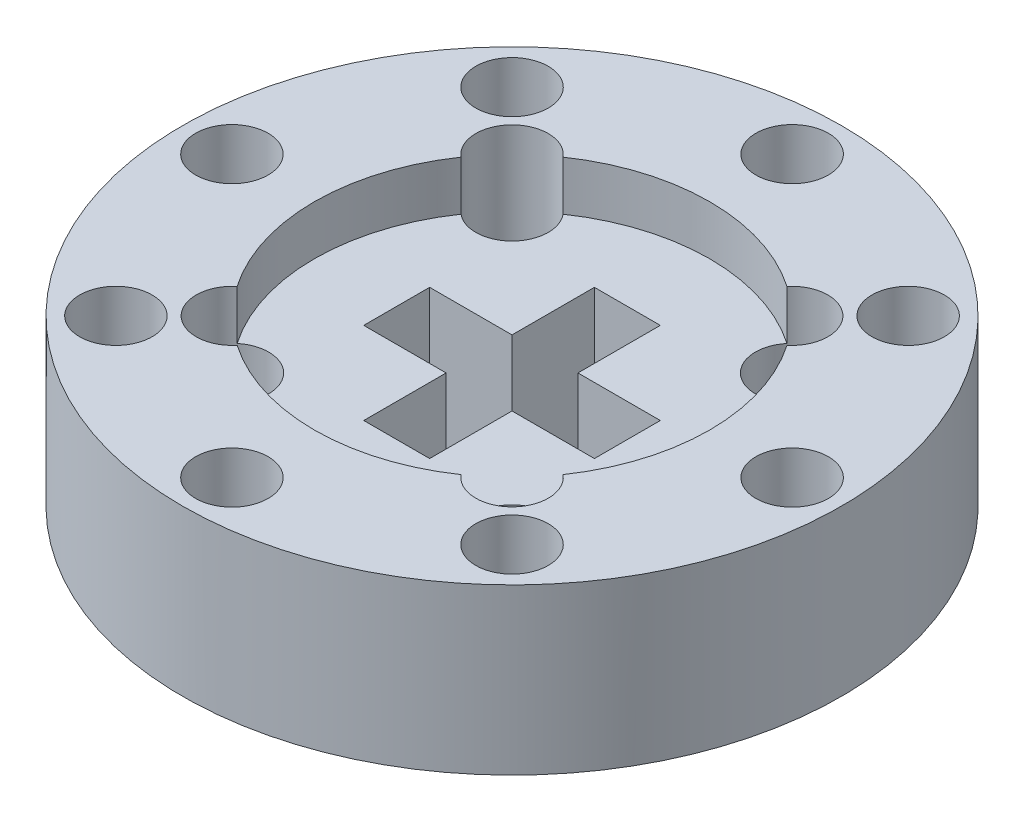
SolidWorks part; units mm, degrees
ref_plane "前视基准面" through (0, 0, 0) normal (0, 0, 1) x (1, 0, 0)
ref_plane "上视基准面" through (0, 0, 0) normal (0, 1, 0) x (1, 0, 0)
ref_plane "右视基准面" through (0, 0, 0) normal (1, 0, 0) x (0, 0, -1)
sketch "草图1" plane through (0, 0, 0) normal (0, 1, 0) x (1, 0, 0)
  line L0 (1, 1) -> (3.5, 1)
  line L1 (-1, 3.5) -> (1, 3.5)
  line L2 (-1, 3.5) -> (-1, 1)
  line L3 (-1, -3.5) -> (1, -3.5)
  line L4 (1, 3.5) -> (1, 1)
  line L5 (0, 3.5) -> (0, -3.5) construction
  line L6 (-3.5, 0) -> (3.5, 0) construction
  line L7 (-3.5, 1) -> (-1, 1)
  line L8 (-3.5, 1) -> (-3.5, -1)
  line L9 (-3.5, -1) -> (-1, -1)
  line L10 (3.5, 1) -> (3.5, -1)
  line L14 (-1, -1) -> (-1, -3.5)
  line L17 (1, -1) -> (1, -3.5)
  line L18 (1, -1) -> (3.5, -1)
  circle A0 centre (0, 0) radius 10
  point P14 (0, 0)
  dimension "D1" = 20
  dimension "D2" = 2
  dimension "D3" = 2
  dimension "D4" = 7
  dimension "D5" = 7
extrude "凸台-拉伸1" add sketch "草图1" along normal blind 7
sketch "草图2" plane through (0, 7, 0) normal (0, 1, 0) x (1, 0, 0)
  line L0 (-7.0711, 7.0711) -> (7.0711, -7.0711) construction
  line L1 (0, 0) -> (4.2904, 4.2904) construction
  circle A0 centre (0, 0) radius 10 construction
  circle A1 centre (-6.0104, 6.0104) radius 1.1
  circle A2 centre (6.0104, -6.0104) radius 1.1
  dimension "D2" = 2.2
  dimension "D1" = 17
extrude "切除-拉伸1" cut sketch "草图2" against normal through all
pattern_circular "阵列(圆周)1" count 4 every 45 about axis through (0, 0, 0) along (0, 1, 0) of "切除-拉伸1"
sketch "草图3" plane through (0, 7, 0) normal (0, 1, 0) x (1, 0, 0)
  line L0 (-6.0104, 6.0104) -> (6.0104, -6.0104) construction
  line L1 (0, 0) -> (4.0503, 4.0503) construction
  circle A0 centre (-4.2426, 4.2426) radius 1.1
  circle A1 centre (4.2426, -4.2426) radius 1.1
  circle A2 centre (-6.0104, 6.0104) radius 1.1 construction
  point P11 (-3.6662, 3.6662)
  point P12 (3.2127, -3.2127)
  dimension "D1" = 12
extrude "切除-拉伸2" cut sketch "草图3" against normal through all
pattern_circular "阵列(圆周)2" count 2 every 90 about axis through (0, 0, 0) along (0, 1, 0) of "切除-拉伸2"
sketch "草图4" plane through (0, 7, 0) normal (0, 1, 0) x (1, 0, 0)
  circle A0 centre (0, 0) radius 6
  dimension "D1" = 12
extrude "切除-拉伸3" cut sketch "草图4" against normal blind 1.5
sketch "草图5" plane through (0, 0, 0) normal (0, -1, 0) x (1, 0, 0)
  circle A0 centre (0, 0) radius 4.5
  circle A1 centre (0, 0) radius 10
  circle A2 centre (0, 0) radius 10 construction
  dimension "D1" = 9
extrude "切除-拉伸4" cut sketch "草图5" against normal blind 2
